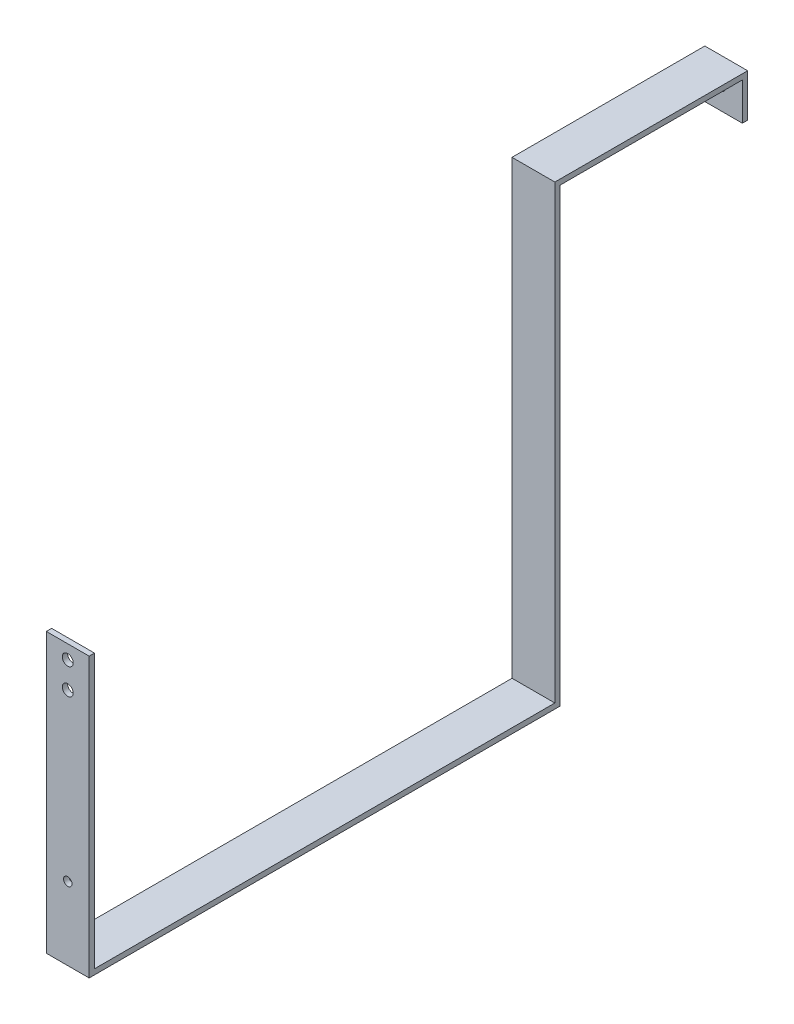
SolidWorks part; units mm, degrees
ref_plane "Alzado" through (0, 0, 0) normal (0, 0, 1) x (1, 0, 0)
ref_plane "Planta" through (0, 0, 0) normal (0, 1, 0) x (1, 0, 0)
ref_plane "Vista lateral" through (0, 0, 0) normal (1, 0, 0) x (0, 0, -1)
sketch "Croquis1" plane through (0, 0, 0) normal (0, 0, 1) x (1, 0, 0)
  line L1 (-25.4, -3.155) -> (25.4, -3.155)
  line L2 (-25.4, -3.155) -> (-25.4, 3.155)
  line L3 (-25.4, 3.155) -> (25.4, 3.155)
  line L4 (25.4, -3.155) -> (25.4, 3.155)
  line L5 (-25.4, -3.155) -> (25.4, 3.155) construction
  line L6 (-25.4, 3.155) -> (25.4, -3.155) construction
  point P0 (0, 0)
  dimension "D1" = 6.31
  dimension "D2" = 50.8
extrude "Saliente-Extruir1" add sketch "Croquis1" along normal blind 228.75
sketch "Croquis2" plane through (0, -3.155, 0) normal (0, -1, 0) x (1, 0, 0)
  line L0 (25.4, 228.75) -> (-25.4, 228.75)
  line L1 (-25.4, 228.75) -> (-25.4, 222.44)
  line L2 (-25.4, 228.75) -> (-25.4, 0) construction
  line L3 (-25.4, 222.44) -> (25.4, 222.44)
  line L4 (25.4, 228.75) -> (25.4, 0) construction
  line L5 (25.4, 222.44) -> (25.4, 228.75)
  dimension "D1" = 6.31
extrude "Saliente-Extruir2" add sketch "Croquis2" along normal blind 535.27
sketch "Croquis3" plane through (0, 0, 228.75) normal (0, 0, 1) x (1, 0, 0)
  line L0 (-25.4, -538.425) -> (25.4, -538.425)
  line L1 (25.4, -538.425) -> (25.4, -532.115)
  line L2 (25.4, -538.425) -> (25.4, 3.155) construction
  line L3 (25.4, -532.115) -> (-25.4, -532.115)
  line L4 (-25.4, 3.155) -> (-25.4, -538.425) construction
  line L5 (-25.4, -532.115) -> (-25.4, -538.425)
  dimension "D1" = 6.31
extrude "Saliente-Extruir3" add sketch "Croquis3" along normal blind 552.5
sketch "Croquis4" plane through (0, -532.115, 0) normal (0, 1, 0) x (1, 0, 0)
  line L0 (25.4, -781.25) -> (-25.4, -781.25)
  line L1 (-25.4, -781.25) -> (-25.4, -774.94)
  line L2 (-25.4, -774.94) -> (25.4, -774.94)
  line L3 (25.4, -781.25) -> (25.4, -228.75) construction
  line L4 (25.4, -774.94) -> (25.4, -781.25)
  dimension "D1" = 6.31
extrude "Saliente-Extruir4" add sketch "Croquis4" along normal blind 324.39
sketch "Croquis5" plane through (0, 3.155, 0) normal (0, 1, 0) x (1, 0, 0)
  line L0 (-25.4, 0) -> (25.4, 0)
  line L1 (25.4, 0) -> (25.4, -6.31)
  line L2 (25.4, -228.75) -> (25.4, 0) construction
  line L3 (25.4, -6.31) -> (-25.4, -6.31)
  line L4 (-25.4, -228.75) -> (-25.4, 0) construction
  line L5 (-25.4, -6.31) -> (-25.4, 0)
  dimension "D1" = 6.31
extrude "Saliente-Extruir5" add sketch "Croquis5" against normal blind 50.8
sketch "Croquis7" plane through (0, 0, 6.31) normal (0, 0, 1) x (1, 0, 0)
  line L0 (-25.4, -47.645) -> (25.4, 3.155) construction
  line L1 (25.4, 3.155) -> (0, -22.245) construction
  line L2 (0, -22.245) -> (12.7, -9.545) construction
  line L3 (12.7, -9.545) -> (12.7, -2.1449) construction
  line L4 (0, -22.245) -> (-25.4, -47.645) construction
  line L5 (-25.4, -47.645) -> (-12.7, -34.945) construction
  line L6 (-12.7, -34.945) -> (-12.7, 26.2422) construction
  circle A2 centre (0, -22.245) radius 5
  dimension "D3" = 10
extrude "Cortar-Extruir2" cut sketch "Croquis7" against normal blind 415.8
sketch "Croquis8" plane through (0, 0, 781.25) normal (0, 0, 1) x (1, 0, 0)
  line L0 (0, -207.725) -> (0, -224.225) construction
  line L1 (-25.4, -207.725) -> (25.4, -207.725) construction
  line L2 (0, -224.225) -> (0, -255.225) construction
  circle A0 centre (0, -224.225) radius 6.5
  circle A1 centre (0, -255.225) radius 6.5
  dimension "D3" = 13
  dimension "D4" = 13
  dimension "D1" = 16.5
  dimension "D2" = 31
extrude "Cortar-Extruir3" cut sketch "Croquis8" against normal blind 10
sketch "Croquis9" plane through (0, 0, 781.25) normal (0, 0, 1) x (1, 0, 0)
  line L0 (0, -538.425) -> (0, -445.025) construction
  line L1 (-25.4, -538.425) -> (25.4, -538.425) construction
  line L2 (0, -445.025) -> (0, -451.925) construction
  line L3 (0, -451.925) -> (0, -428.925) construction
  circle A0 centre (0, -445.025) radius 3.5 construction
  circle A1 centre (0, -451.925) radius 5
  circle A2 centre (0, -428.925) radius 3.5 construction
  dimension "D4" = 7
  dimension "D5" = 7
  dimension "D6" = 10
  dimension "D1" = 86.5
  dimension "D3" = 23
extrude "Cortar-Extruir4" cut sketch "Croquis9" against normal blind 35
